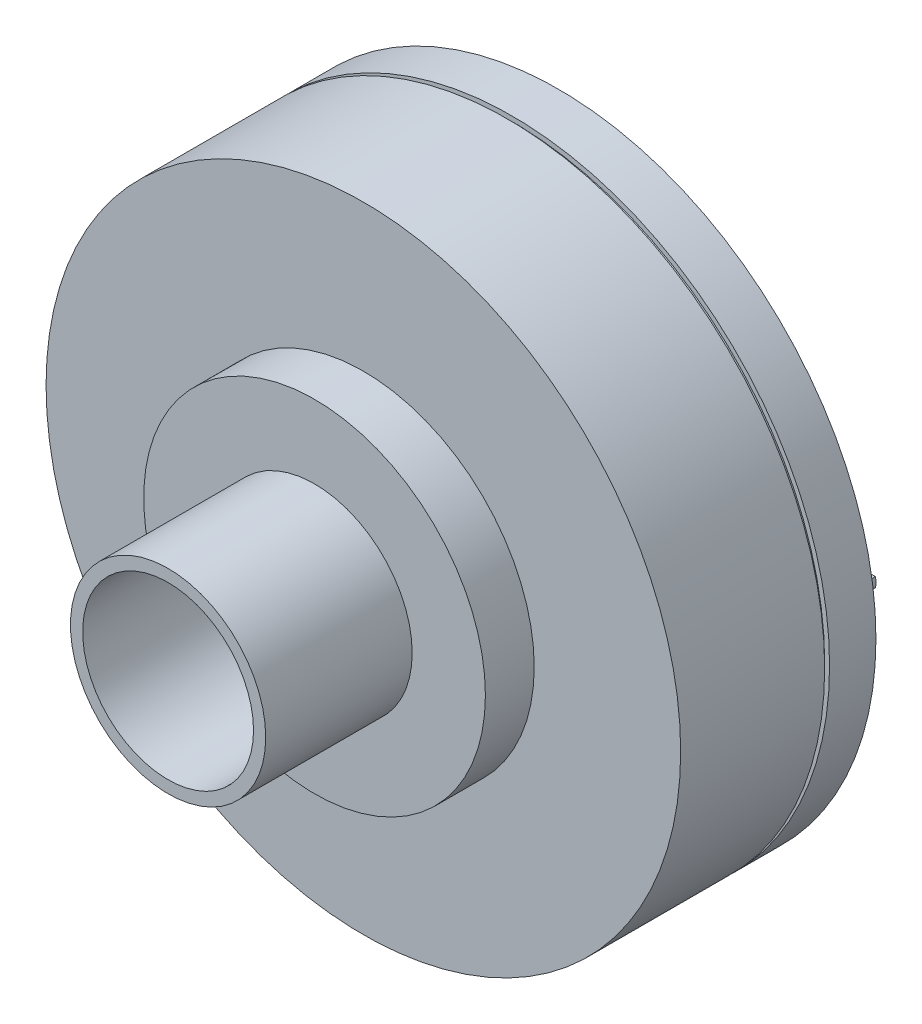
SolidWorks part; units mm, degrees
ref_plane "Alzado" through (0, 0, 0) normal (0, 0, 1) x (1, 0, 0)
ref_plane "Planta" through (0, 0, 0) normal (0, 1, 0) x (1, 0, 0)
ref_plane "Vista lateral" through (0, 0, 0) normal (1, 0, 0) x (0, 0, -1)
sketch "Croquis2" plane through (0, 0, 0) normal (1, 0, 0) x (0, 0, -1)
  line L0 (0, 0) -> (0, 6.5)
  line L1 (0, 6.5) -> (-0.95, 6.5)
  line L2 (-4, 6.5) -> (-4, 3.5)
  line L3 (-4, 3.5) -> (-5, 3.5)
  line L4 (-5, 3.5) -> (-5, 2)
  line L5 (-5, 2) -> (-8, 2)
  line L6 (-8, 2) -> (-8, 1.75)
  line L7 (-8, 1.75) -> (-4, 1.75)
  line L8 (-4, 1.75) -> (-4, 0)
  line L9 (-4, 0) -> (0, 0)
  line L10 (-0.95, 6.5) -> (-0.95, 6.4)
  line L11 (-0.95, 6.4) -> (-1.05, 6.4)
  line L12 (-1.05, 6.4) -> (-1.05, 6.5)
  line L13 (-1.05, 6.5) -> (-4, 6.5)
  dimension "D1" = 6.5
  dimension "D2" = 4
  dimension "D3" = 0.95
  dimension "D4" = 3
  dimension "D5" = 4
  dimension "D6" = 2.95
  dimension "D7" = 0.1
  dimension "D8" = 1.75
  dimension "D9" = 4
revolve "Revolución1" add sketch "Croquis2" angle 360 about L9
sketch "Croquis3" plane through (0, 0, 0) normal (0, 0, -1) x (-1, 0, 0)
  line L0 (0, 0) -> (0, -2) construction
  line L1 (0, -2) -> (0, -3) construction
  line L2 (0, -3) -> (-2, -3) construction
  line L3 (0, -3) -> (2, -3) construction
  circle A0 centre (0, 0) radius 0.5 construction
  circle A1 centre (0, 0) radius 1 construction
  circle A2 centre (-2, -3) radius 0.5
  circle A3 centre (2, -3) radius 0.5
  circle A4 centre (0, -2) radius 0.5
  dimension "D1" = 1
  dimension "D2" = 2
  dimension "D7" = 1
  dimension "D3" = 2
  dimension "D4" = 1
  dimension "D5" = 2
  dimension "D6" = 2
extrude "Cortar-Extruir1" cut sketch "Croquis3" against normal blind 1
sketch "Croquis5" plane through (0, 0, 1) normal (0, 0, -1) x (-1, 0, 0)
  line L1 (-0.4899, -1.9) -> (0.4899, -1.9)
  line L3 (-0.4899, -2.1) -> (0.4899, -2.1)
  line L5 (-0.4899, -1.9) -> (0.4899, -2.1) construction
  line L6 (-0.4899, -2.1) -> (0.4899, -1.9) construction
  line L7 (1.5101, -2.9) -> (2.4899, -2.9)
  line L9 (1.5101, -3.1) -> (2.4899, -3.1)
  line L11 (1.5101, -2.9) -> (2.4899, -3.1) construction
  line L12 (1.5101, -3.1) -> (2.4899, -2.9) construction
  line L13 (-2.4899, -2.9) -> (-1.5101, -2.9)
  line L15 (-2.4899, -3.1) -> (-1.5101, -3.1)
  line L17 (-2.4899, -2.9) -> (-1.5101, -3.1) construction
  line L18 (-2.4899, -3.1) -> (-1.5101, -2.9) construction
  circle A0 centre (0, -2) radius 0.5 construction
  circle A1 centre (2, -3) radius 0.5 construction
  circle A2 centre (-2, -3) radius 0.5 construction
  arc A3 (0.4899, -2.1) -> (0.4899, -1.9) centre (0, -2) ccw
  arc A4 (-0.4899, -1.9) -> (-0.4899, -2.1) centre (0, -2) ccw
  arc A5 (2.4899, -3.1) -> (2.4899, -2.9) centre (2, -3) ccw
  arc A6 (1.5101, -2.9) -> (1.5101, -3.1) centre (2, -3) ccw
  arc A7 (-1.5101, -3.1) -> (-1.5101, -2.9) centre (-2, -3) ccw
  arc A8 (-2.4899, -2.9) -> (-2.4899, -3.1) centre (-2, -3) ccw
  point P0 (0, -2)
  point P8 (2, -3)
  point P16 (-2, -3)
  dimension "D1" = 0.2
  dimension "D2" = 0.2
  dimension "D3" = 0.2
extrude "Saliente-Extruir3" add sketch "Croquis5" along normal blind 5
